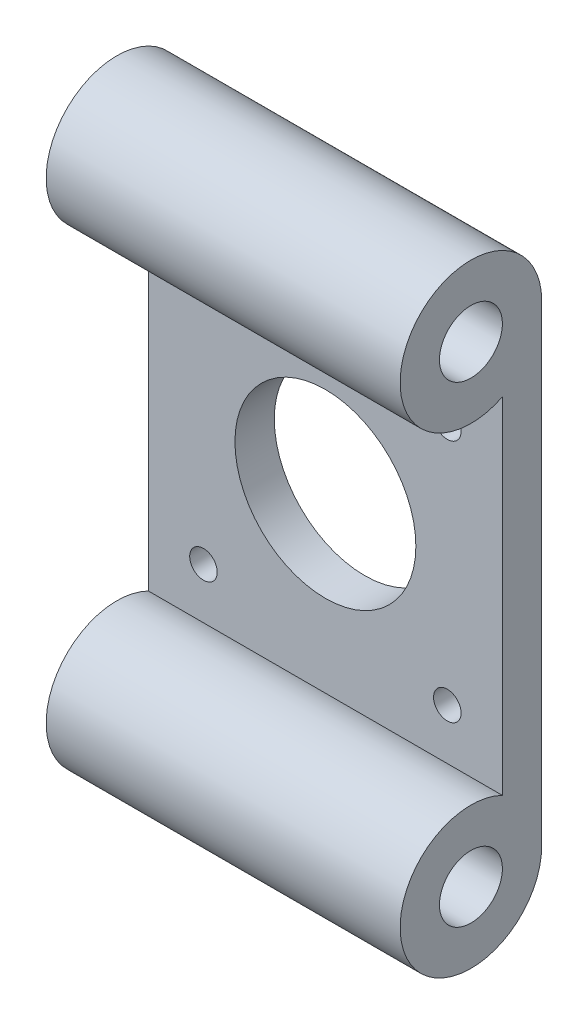
SolidWorks part; units mm, degrees
material "ABS"
ref_plane "Plano frontal" through (0, 0, 0) normal (0, 0, 1) x (1, 0, 0)
ref_plane "Plano superior" through (0, 0, 0) normal (0, 1, 0) x (1, 0, 0)
ref_plane "Plano direito" through (0, 0, 0) normal (1, 0, 0) x (0, 0, -1)
sketch "Esboço1" plane through (0, 0, 0) normal (0, 0, 1) x (1, 0, 0)
  line L1 (-22.5, 22.5) -> (22.5, 22.5)
  line L2 (-22.5, 22.5) -> (-22.5, -22.5)
  line L3 (-22.5, -22.5) -> (22.5, -22.5)
  line L4 (22.5, 22.5) -> (22.5, -22.5)
  line L5 (-22.5, 22.5) -> (22.5, -22.5) construction
  line L6 (-22.5, -22.5) -> (22.5, 22.5) construction
  circle A0 centre (-15.5, 15.5) radius 1.75
  circle A1 centre (15.5, 15.5) radius 1.75
  circle A2 centre (15.5, -15.5) radius 1.75
  circle A3 centre (-15.5, -15.5) radius 1.75
  circle A4 centre (0, 0) radius 11.5
  point P0 (0, 0)
  point P17 (0, 0)
  dimension "D2" = 3.5
  dimension "D4" = 31
  dimension "D5" = 23
  dimension "D1" = 45
  dimension "D3" = 4
extrude "Ressalto-extrusão1" add sketch "Esboço1" along normal blind 5
sketch "Esboço3" plane through (-22.5, 0, 0) normal (-1, 0, 0) x (0, 0, 1)
  line L0 (0, 30) -> (0, 21.9377)
  line L1 (0, 22.5) -> (0, -22.5) construction
  line L3 (0, 0) -> (21.5803, 0) construction
  line L5 (5, 21.9377) -> (0, 21.9377)
  line L6 (5, -21.9377) -> (0, -21.9377)
  line L7 (0, -21.9377) -> (0, -30)
  circle A0 centre (9, 30) radius 4
  arc A1 (5, 21.9377) -> (0, 30) centre (9, 30) ccw
  arc A2 (5, -21.9377) -> (0, -30) centre (9, -30) cw
  circle A3 centre (9, -30) radius 4
  point P14 (5, 0)
  dimension "D1" = 18
  dimension "D2" = 8
  dimension "D3" = 30
extrude "Ressalto-extrusão2" add sketch "Esboço3" against normal up to surface (45 mm away) up to face at (22.5, 0, 2.5)
